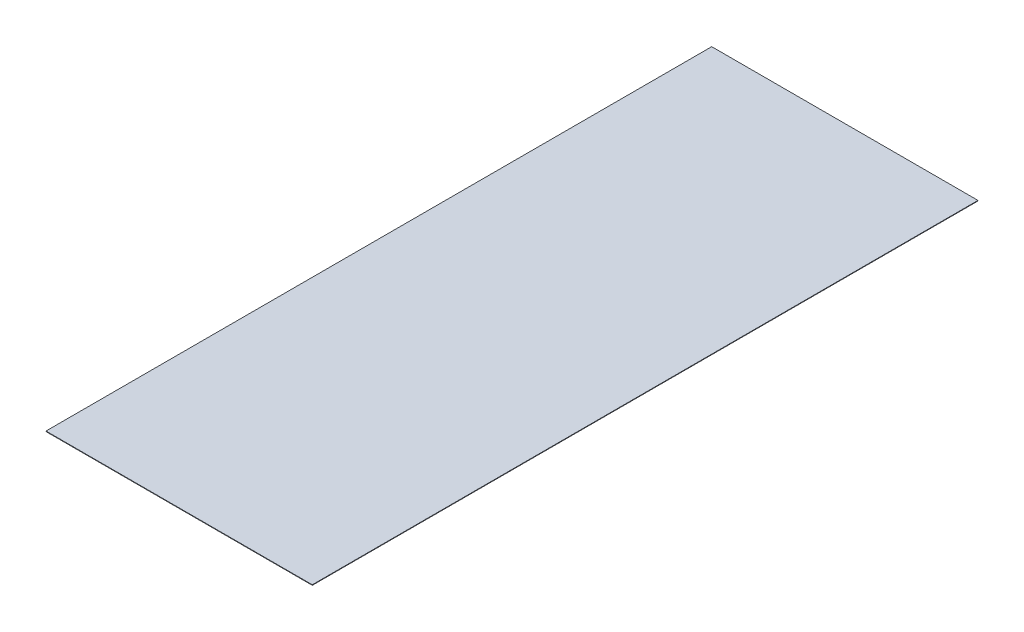
SolidWorks part; units mm, degrees
material "ASTM A36 Acero"
ref_plane "Alzado" through (0, 0, 0) normal (0, 0, 1) x (1, 0, 0)
ref_plane "Planta" through (0, 0, 0) normal (0, 1, 0) x (1, 0, 0)
ref_plane "Vista lateral" through (0, 0, 0) normal (1, 0, 0) x (0, 0, -1)
sketch "Croquis1" plane through (0, 0, 0) normal (0, 1, 0) x (1, 0, 0)
  line L1 (-609.6, -1524) -> (609.6, -1524)
  line L2 (-609.6, -1524) -> (-609.6, 1524)
  line L3 (-609.6, 1524) -> (609.6, 1524)
  line L4 (609.6, -1524) -> (609.6, 1524)
  line L5 (-609.6, -1524) -> (609.6, 1524) construction
  line L6 (-609.6, 1524) -> (609.6, -1524) construction
  point P0 (0, 0)
  dimension "D1" = 3048
  dimension "D2" = 1219.2
extrude "Saliente-Extruir1" add sketch "Croquis1" along normal blind 2.3
